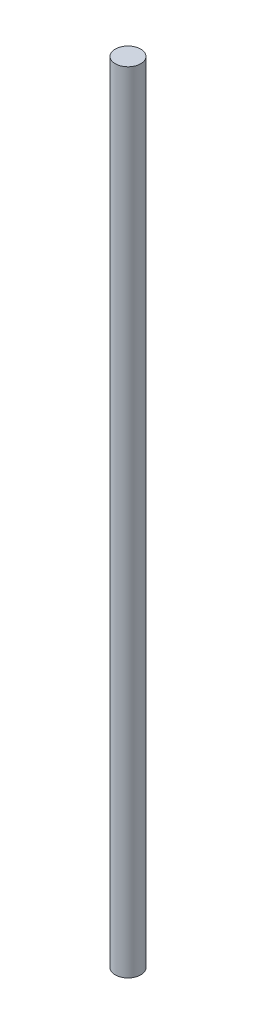
SolidWorks part; units mm, degrees
ref_plane "Front Plane" through (0, 0, 0) normal (0, 0, 1) x (1, 0, 0)
ref_plane "Top Plane" through (0, 0, 0) normal (0, 1, 0) x (1, 0, 0)
ref_plane "Right Plane" through (0, 0, 0) normal (1, 0, 0) x (0, 0, -1)
sketch "Sketch1" plane through (0, 0, 0) normal (0, 1, 0) x (1, 0, 0)
  circle A0 centre (0, 0) radius 3.175
  dimension "D1" = 6.35
extrude "Boss-Extrude1" add sketch "Sketch1" along normal blind 196.85 contours A0
equation "\"L\"= \"RodLength@J2Rod.Assembly\""
equation "\"D1@Boss-Extrude1\"=\"RodMax\""
equation "\"centerBotDist\"= 5 / 8"
equation "\"RodMax\"= \"L\" - 2 * \"centerBotDist\""
equation "\"Wiggle\"= .125"
equation "\"ThreadRodLength\"= \"RodMax\" - \"Wiggle\""
